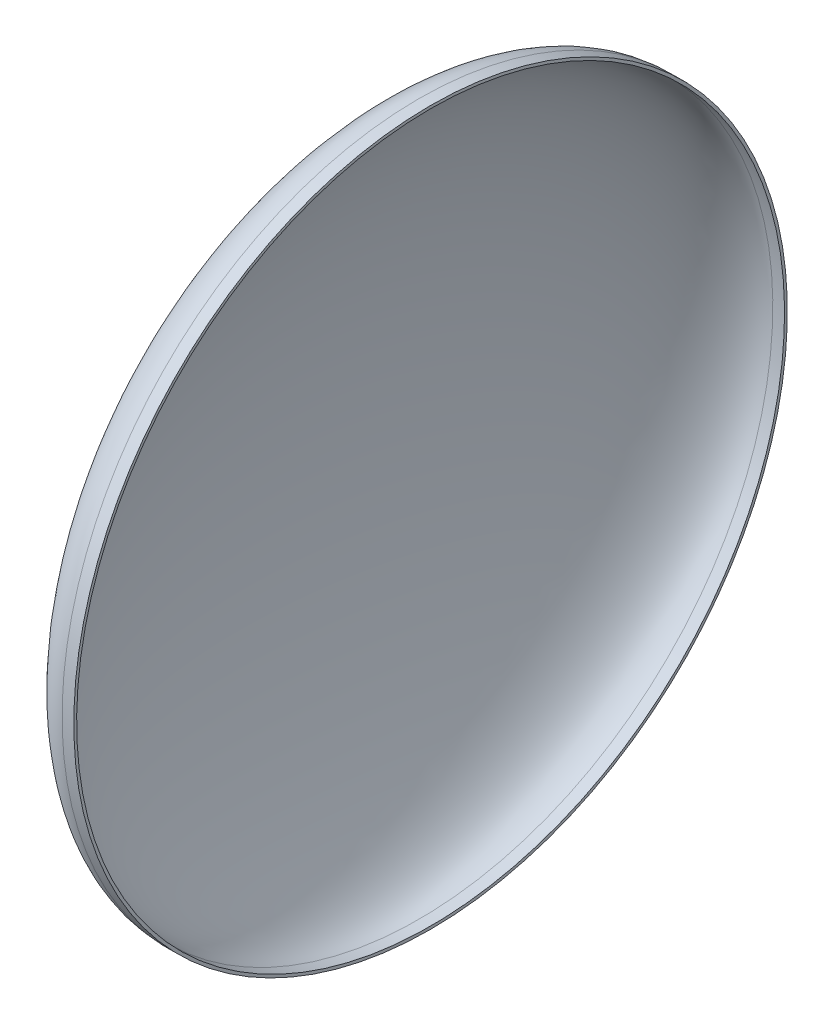
SolidWorks part; units mm, degrees
material "ASTM A36 Steel"
ref_plane "Front Plane" through (0, 0, 0) normal (0, 0, 1) x (1, 0, 0)
ref_plane "Top Plane" through (0, 0, 0) normal (0, 1, 0) x (1, 0, 0)
ref_plane "Right Plane" through (0, 0, 0) normal (1, 0, 0) x (0, 0, -1)
sketch "Sketch1" plane through (0, 0, 0) normal (0, 0, 1) x (1, 0, 0)
  line L0 (0, 0) -> (-500, 0) construction
  line L1 (0, 0) -> (0, 1734.846) construction
  line L2 (0, 1520) -> (-50, 1520)
  line L3 (-50, 1520) -> (-50, 0) construction
  line L4 (0, 1508) -> (-50, 1508)
  line L5 (0, 1520) -> (0, 1508)
  line L6 (-488, 0) -> (-500, 0)
  ellipse E0 centre (-50, 0) end of major axis (-50, 1520) minor radius 450 (-50, 1520) -> (-500, 0) ccw
  spline S0 degree 1 poles (-50, 1508) (-488, 0) knots 0 0 1 1 construction
  spline S1 degree 3 poles (-50, 1508) (-53.3535, 1508) (-60.0483, 1507.7224) (-73.4671, 1506.0539) (-90.2958, 1501.8674) (-110.6334, 1493.4055) (-137.9085, 1477.4361) (-172.1314, 1448.5435) (-212.6517, 1399.6187) (-251.9308, 1336.8965) (-289.4123, 1261.0318) (-324.6319, 1172.8124) (-368.0484, 1039.918) (-405.4344, 886.0742) (-435.6461, 715.8049) (-454.5007, 581.1582) (-469.3613, 440.8716) (-480.0818, 296.3115) (-485.4772, 173.4466) (-487.6393, 74.4427) (-488, 24.8034) (-488, 0) knots 0 0 0 0 0.024544 0.049087 0.098175 0.147262 0.19635 0.294524 0.392699 0.490874 0.589049 0.687223 0.785398 0.981748 1.079922 1.178097 1.276272 1.374447 1.472622 1.521709 1.570796 1.570796 1.570796 1.570796
  dimension "D1" = 1520
  dimension "D2" = 50
  dimension "D3" = 500
  dimension "D4" = 12
revolve "Revolve1" add sketch "Sketch1" angle 360 about L0
